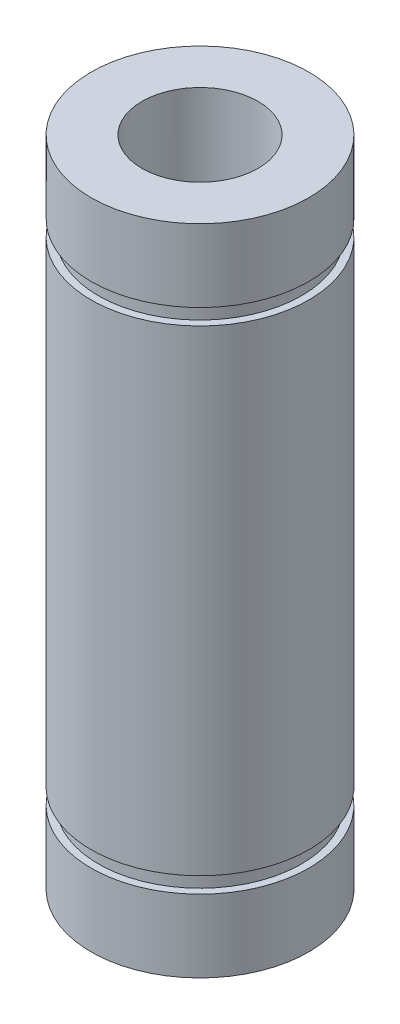
SolidWorks part; units mm, degrees
material "201 Annealed Stainless Steel (SS)"
ref_plane "Front Plane" through (0, 0, 0) normal (0, 0, 1) x (1, 0, 0)
ref_plane "Top Plane" through (0, 0, 0) normal (0, 1, 0) x (1, 0, 0)
ref_plane "Right Plane" through (0, 0, 0) normal (1, 0, 0) x (0, 0, -1)
sketch "Sketch1" plane through (0, 0, 0) normal (0, 1, 0) x (1, 0, 0)
  circle A0 centre (0, 0) radius 4
  circle A1 centre (0, 0) radius 7.5
  dimension "D1" = 8
  dimension "D2" = 15
extrude "Boss-Extrude1" add sketch "Sketch1" along normal blind 5
sketch "Sketch2" plane through (0, 0, 0) normal (0, -1, 0) x (1, 0, 0)
  circle A0 centre (0, 0) radius 4
  circle A1 centre (0, 0) radius 7
  dimension "D1" = 14
extrude "Boss-Extrude2" add sketch "Sketch2" along normal blind 1.1
sketch "Sketch3" plane through (0, -1.1, 0) normal (0, -1, 0) x (1, 0, 0)
  circle A0 centre (0, 0) radius 7.5
  circle A1 centre (0, 0) radius 4
extrude "Boss-Extrude3" add sketch "Sketch3" along normal blind 32.8
sketch "Sketch5" plane through (0, -33.9, 0) normal (0, -1, 0) x (1, 0, 0)
  circle A0 centre (0, 0) radius 4
  circle A1 centre (0, 0) radius 7
  dimension "D1" = 14
extrude "Boss-Extrude5" add sketch "Sketch5" along normal blind 1.1
sketch "Sketch6" plane through (0, -35, 0) normal (0, -1, 0) x (1, 0, 0)
  circle A0 centre (0, 0) radius 4
  circle A1 centre (0, 0) radius 7.5
  dimension "D1" = 15
extrude "Boss-Extrude6" add sketch "Sketch6" along normal blind 5
